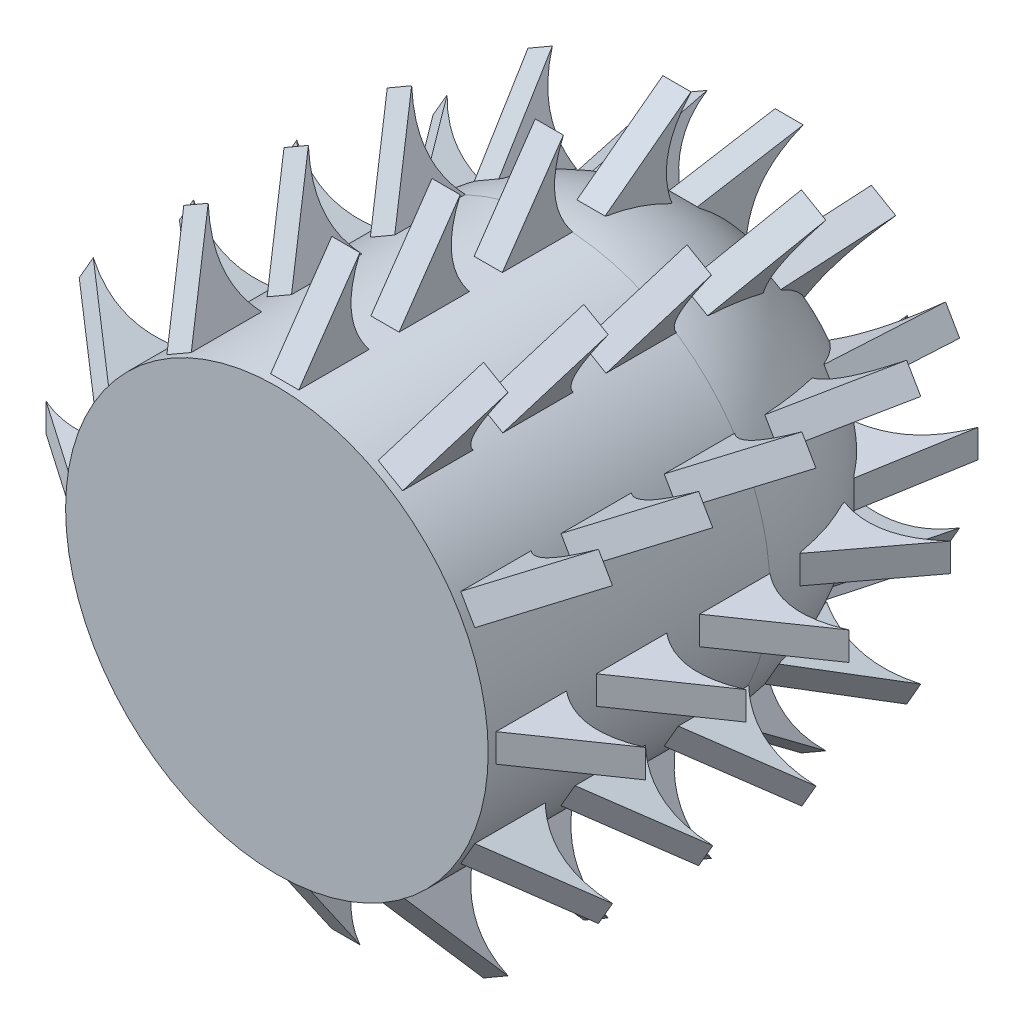
SolidWorks part; units mm, degrees
ref_plane "정면" through (0, 0, 0) normal (0, 0, 1) x (1, 0, 0)
ref_plane "윗면" through (0, 0, 0) normal (0, 1, 0) x (1, 0, 0)
ref_plane "우측면" through (0, 0, 0) normal (1, 0, 0) x (0, 0, -1)
sketch "스케치1" plane through (0, 0, 0) normal (0, 0, 1) x (1, 0, 0)
  circle A0 centre (0, 0) radius 15
  dimension "D1" = 30
extrude "보스-돌출1" add sketch "스케치1" along normal blind 20
sketch "스케치3" plane through (0, 0, 0) normal (1, 0, 0) x (0, 0, -1)
  line L0 (0, 15) -> (0, 0)
  line L1 (0, 0) -> (15, 0)
  arc A0 (0, 15) -> (15, 0) centre (0, 0) cw
revolve "회전1" add sketch "스케치3" angle 360 about L1
sketch "스케치2" plane through (0, 0, 0) normal (0, 1, 0) x (1, 0, 0)
  line L3 (15, -12.3272) -> (15, -7.3272)
  line L4 (15, -5) -> (15, 0)
  line L5 (12.1166, 8.8424) -> (8.5372, 12.3335)
  line L6 (14.8233, 2.2958) -> (13.2452, 7.0402)
  line L7 (15, -19.4425) -> (15, -14.4425)
  line L8 (6.4604, 13.5375) -> (1.6521, 14.9087)
  line L9 (6.4604, 13.5375) -> (4.0105, 20.7645)
  line L10 (12.1166, 8.8424) -> (13.3947, 16.3656)
  line L11 (14.8233, 2.2958) -> (19.4113, 8.3935)
  line L12 (15, -5) -> (21.2781, -0.6621)
  line L13 (15, -12.3272) -> (21.2781, -7.9893)
  line L14 (15, -19.4425) -> (21.2781, -15.1045)
  circle A1 centre (0, 0) radius 15 construction
  spline S0 degree 2 poles (21.2781, -7.9893) (17.7305, -9.5279) (15, -7.3272) knots 0 0 0 1 1 1
  spline S2 degree 2 poles (21.2781, -0.6621) (17.7305, -2.2006) (15, 0) knots 0 0 0 1 1 1
  spline S4 degree 2 poles (13.3947, 16.3656) (12.0191, 12.7517) (8.5372, 12.3335) knots 0 0 0 1 1 1
  spline S6 degree 2 poles (19.4113, 8.3935) (16.5307, 5.8139) (13.2452, 7.0402) knots 0 0 0 1 1 1
  spline S8 degree 2 poles (21.2781, -15.1045) (17.7305, -16.6431) (15, -14.4425) knots 0 0 0 1 1 1
  spline S10 degree 2 poles (4.0105, 20.7645) (4.5172, 16.9311) (1.6521, 14.9087) knots 0 0 0 1 1 1
extrude "보스-돌출2" add sketch "스케치2" along normal mid plane 2 separate body
pattern_circular "원형 패턴3" count 12 over 360 about axis through (0, 0, 20) along (0, 0, -1) of bodies 126 103 102 140 139 141
pattern_circular "원형 패턴4" count 3 over 360 about axis through (0, 0, 20) along (0, 0, -1) of bodies 141
ref_plane "평면1" through (0, 0, 0) normal (0.7071, -0.7071, 0) x (-0.7071, -0.7071, 0)
combine bodies "합치기3" operation type add bodies to combine 172 161 138
